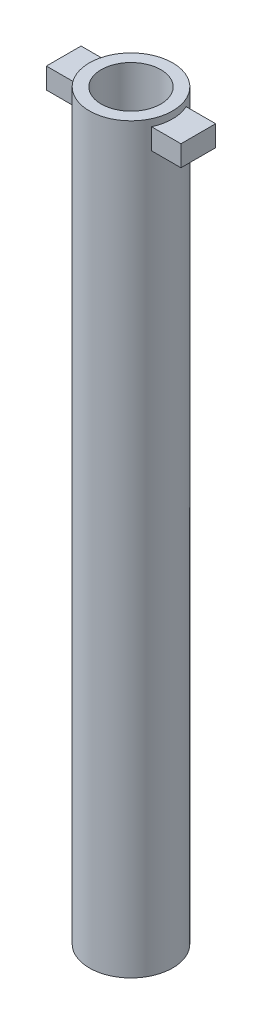
SolidWorks part; units mm, degrees
ref_plane "前视基准面" through (0, 0, 0) normal (0, 0, 1) x (1, 0, 0)
ref_plane "上视基准面" through (0, 0, 0) normal (0, 1, 0) x (1, 0, 0)
ref_plane "右视基准面" through (0, 0, 0) normal (1, 0, 0) x (0, 0, -1)
other "Configuration Table"
sketch "草图1" plane through (0, 0, 0) normal (0, 0, 1) x (1, 0, 0)
  line L0 (0, 0) -> (6, 0)
  line L1 (6, 0) -> (6, 107)
  line L2 (6, 107) -> (0, 107)
  line L3 (0, 107) -> (0, 0)
  line L4 (0, 0) -> (0, 107) construction
  dimension "radius" = 6
  dimension "height" = 107
revolve "Output_tube" add sketch "草图1" angle 360 about L4
ref_plane "Key_plane" through (0, 0, -2.5) normal (0, 0, 1) x (1, 0, 0)
sketch "草图3" plane through (0, 0, -2.5) normal (0, 0, 1) x (1, 0, 0)
  line L0 (-9.7, 103) -> (9.7, 103)
  line L1 (9.7, 103) -> (9.7, 106)
  line L2 (9.7, 106) -> (-9.7, 106)
  line L3 (-9.7, 106) -> (-9.7, 103)
  dimension "x0" = 9.7
  dimension "x1" = 9.7
  dimension "y0" = 103
  dimension "y2" = 106
extrude "Internal_output_key" add sketch "草图3" along normal blind 5
sketch "草图4" plane through (0, 107, 0) normal (0, 1, 0) x (1, 0, 0)
  circle A0 centre (0, 0) radius 4.3
  dimension "diameter" = 8.6
extrude "Screw_clearance" cut sketch "草图4" against normal blind 52
